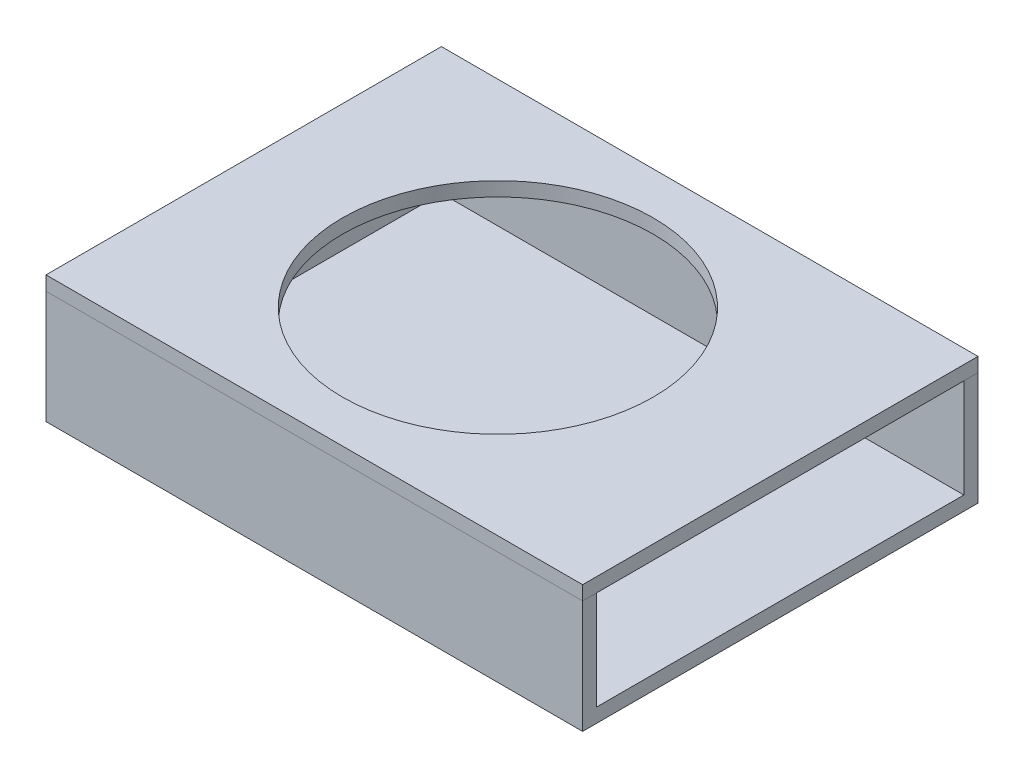
SolidWorks part; units mm, degrees
ref_plane "정면" through (0, 0, 0) normal (0, 0, 1) x (1, 0, 0)
ref_plane "윗면" through (0, 0, 0) normal (0, 1, 0) x (1, 0, 0)
ref_plane "우측면" through (0, 0, 0) normal (1, 0, 0) x (0, 0, -1)
sketch "스케치1" plane through (0, 0, 0) normal (0, 1, 0) x (1, 0, 0)
  line L1 (19, -14) -> (-19, -14)
  line L2 (19, -14) -> (19, 14)
  line L3 (19, 14) -> (-19, 14)
  line L4 (-19, -14) -> (-19, 14)
  line L5 (19, -14) -> (-19, 14) construction
  line L6 (19, 14) -> (-19, -14) construction
  point P0 (0, 0)
  dimension "D1" = 38
  dimension "D2" = 28
extrude "보스-돌출1" add sketch "스케치1" along normal blind 8
sketch "스케치2" plane through (0, 0, 0) normal (0, 1, 0) x (1, 0, 0)
  line L0 (19, 14) -> (-19, 14) construction
  line L1 (-18, 13) -> (19, 13)
  line L2 (-18, 13) -> (-18, -13)
  line L3 (-18, -13) -> (19, -13)
  line L4 (19, 13) -> (19, -13)
  line L5 (-19, 14) -> (-19, -14) construction
  dimension "D1" = 1
  dimension "D2" = 26
  dimension "D3" = 37
  dimension "D4" = 1
extrude "컷-돌출1" cut sketch "스케치2" along normal blind 7 from offset 1
sketch "스케치4" plane through (0, 0, 0) normal (0, 1, 0) x (1, 0, 0)
  line L1 (19, -14) -> (-19, -14)
  line L2 (19, -14) -> (19, 14)
  line L3 (19, 14) -> (-19, 14)
  line L4 (-19, -14) -> (-19, 14)
  line L5 (19, -14) -> (-19, 14) construction
  line L6 (19, 14) -> (-19, -14) construction
  point P0 (0, 0)
extrude "보스-돌출3" add sketch "스케치4" along normal blind 1 from offset 8 separate body
sketch "스케치5" plane through (0, 0, 0) normal (0, 1, 0) x (1, 0, 0)
  line L0 (-19, 14) -> (-19, -14) construction
  line L3 (19, 14) -> (-19, 14) construction
  circle A0 centre (-1, 0) radius 11
  dimension "D1" = 22
  dimension "D2" = 7
  dimension "D3" = 3
extrude "컷-돌출2" cut sketch "스케치5" against normal blind 1 from surface at 9 starting at face at (0, 9, 0)
